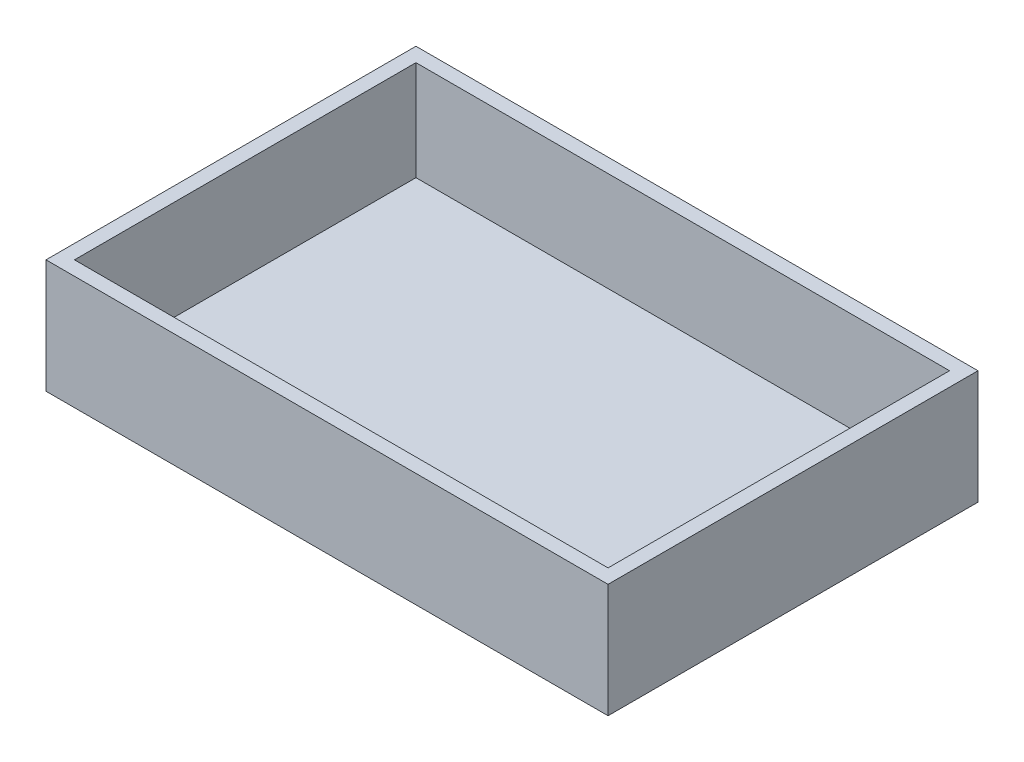
SolidWorks part; units mm, degrees
ref_plane "Front Plane" through (0, 0, 0) normal (0, 0, 1) x (1, 0, 0)
ref_plane "Top Plane" through (0, 0, 0) normal (0, 1, 0) x (1, 0, 0)
ref_plane "Right Plane" through (0, 0, 0) normal (1, 0, 0) x (0, 0, -1)
sketch "Sketch1" plane through (0, 0, 0) normal (0, 1, 0) x (1, 0, 0)
  line L0 (-197.5, -130) -> (197.5, -130)
  line L1 (-187.5, 120) -> (187.5, 120)
  line L2 (-187.5, 120) -> (-187.5, -120)
  line L3 (-187.5, -120) -> (187.5, -120)
  line L4 (187.5, 120) -> (187.5, -120)
  line L5 (-187.5, 120) -> (187.5, -120) construction
  line L6 (-187.5, -120) -> (187.5, 120) construction
  line L7 (197.5, 130) -> (197.5, -130)
  line L8 (-197.5, 130) -> (197.5, 130)
  line L9 (-197.5, 130) -> (-197.5, -130)
  point P0 (0, 0)
  dimension "D1" = 240
  dimension "D2" = 375
  dimension "D3" = 10
extrude "Boss-Extrude1" add sketch "Sketch1" along normal blind 70
sketch "Sketch2" plane through (0, 0, 0) normal (0, -1, 0) x (1, 0, 0)
  line L4 (-197.5, 130) -> (-197.5, -130)
  line L5 (-197.5, -130) -> (197.5, -130)
  line L6 (197.5, -130) -> (197.5, 130)
  line L7 (197.5, 130) -> (-197.5, 130)
  line L8 (-197.5, 130) -> (-197.5, -130)
  line L9 (-197.5, -130) -> (197.5, -130)
  line L10 (197.5, -130) -> (197.5, 130)
  line L11 (197.5, 130) -> (-197.5, 130)
  dimension "D1" = 0
extrude "Boss-Extrude2" add sketch "Sketch2" along normal blind 10
